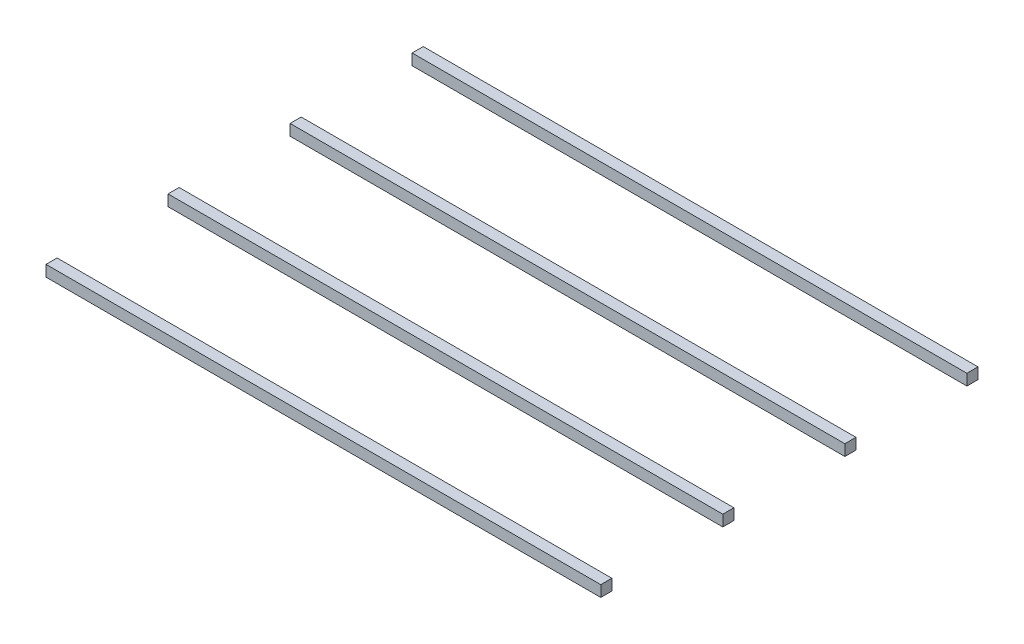
SolidWorks part; units mm, degrees
ref_plane "Front Plane" through (0, 0, 0) normal (0, 0, 1) x (1, 0, 0)
ref_plane "Top Plane" through (0, 0, 0) normal (0, 1, 0) x (1, 0, 0)
ref_plane "Right Plane" through (0, 0, 0) normal (1, 0, 0) x (0, 0, -1)
sketch "Sketch1" plane through (0, 0, 0) normal (0, 1, 0) x (1, 0, 0)
  line L1 (-24.5317, 6.4777) -> (25.4683, 6.4777)
  line L2 (-24.5317, 6.4777) -> (-24.5317, 5.4777)
  line L3 (-24.5317, 5.4777) -> (25.4683, 5.4777)
  line L4 (25.4683, 6.4777) -> (25.4683, 5.4777)
  line L5 (-24.5317, -4.5223) -> (25.4683, -4.5223)
  line L6 (-24.5317, -4.5223) -> (-24.5317, -5.5223)
  line L7 (-24.5317, -5.5223) -> (25.4683, -5.5223)
  line L8 (25.4683, -4.5223) -> (25.4683, -5.5223)
  line L9 (-24.5317, -15.5223) -> (25.4683, -15.5223)
  line L10 (-24.5317, -15.5223) -> (-24.5317, -16.5223)
  line L11 (-24.5317, -16.5223) -> (25.4683, -16.5223)
  line L12 (25.4683, -15.5223) -> (25.4683, -16.5223)
  line L13 (-24.5317, -26.5223) -> (25.4683, -26.5223)
  line L14 (-24.5317, -26.5223) -> (-24.5317, -27.5223)
  line L15 (-24.5317, -27.5223) -> (25.4683, -27.5223)
  line L16 (25.4683, -26.5223) -> (25.4683, -27.5223)
  dimension "D1" = 50
  dimension "D2" = 1
  dimension "D3" = 10
  dimension "D4" = 1
  dimension "D5" = 1
  dimension "D6" = 1
  dimension "D7" = 10
  dimension "D8" = 10
extrude "Boss-Extrude1" add sketch "Sketch1" along normal blind 1
